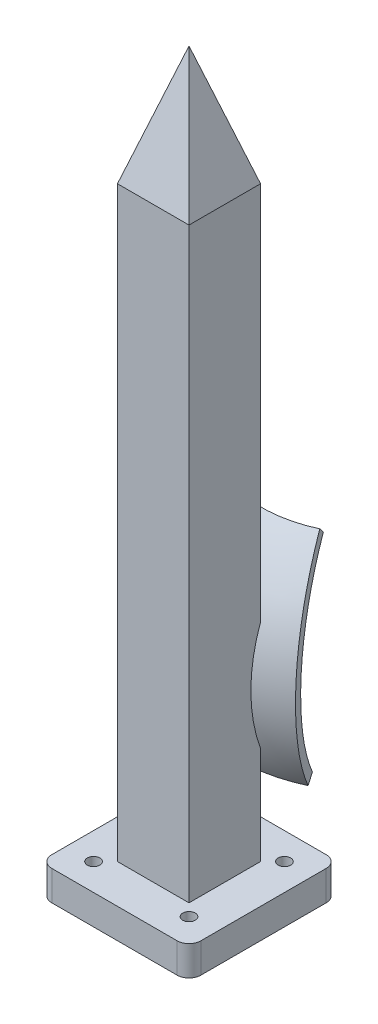
SolidWorks part; units mm, degrees
material "ABS PC"
ref_plane "Front Plane" through (0, 0, 0) normal (0, 0, 1) x (1, 0, 0)
ref_plane "Top Plane" through (0, 0, 0) normal (0, 1, 0) x (1, 0, 0)
ref_plane "Right Plane" through (0, 0, 0) normal (1, 0, 0) x (0, 0, -1)
sketch "Sketch1" plane through (0, 0, 0) normal (0, 1, 0) x (1, 0, 0)
  line L1 (0, 0) -> (25, 0)
  line L2 (0, 0) -> (0, 25)
  line L3 (0, 25) -> (25, 25)
  line L4 (25, 0) -> (25, 25)
  dimension "D1" = 25
  dimension "D2" = 25
extrude "Boss-Extrude1" add sketch "Sketch1" along normal blind 5
sketch "Sketch2" plane through (0, 5, 0) normal (0, 1, 0) x (1, 0, 0)
  line L0 (0, 0) -> (25, 0) construction
  line L1 (0, 25) -> (0, 0) construction
  line L2 (25, 0) -> (25, 25) construction
  line L3 (25, 25) -> (0, 25) construction
  circle A0 centre (4.5, 4.5) radius 1.05
  circle A1 centre (20.5, 4.5) radius 1.05
  circle A2 centre (20.5, 20.5) radius 1.05
  circle A3 centre (4.5, 20.5) radius 1.05
  dimension "D1" = 2.1
  dimension "D4" = 2.1
  dimension "D6" = 2.1
  dimension "D8" = 2.1
  dimension "D2" = 4.5
  dimension "D3" = 4.5
  dimension "D5" = 4.5
  dimension "D7" = 4.5
extrude "Cut-Extrude1" cut sketch "Sketch2" against normal blind 5
fillet "Fillet1" radius 2 4 edges at (0, 2.5, -25) (0, 2.5, 0) (25, 2.5, -25) (25, 2.5, 0)
sketch "Sketch3" plane through (0, 5, 0) normal (0, 1, 0) x (1, 0, 0)
  line L0 (2, 0) -> (23, 0) construction
  line L1 (6.5, 6.5) -> (18.5, 6.5)
  line L2 (6.5, 6.5) -> (6.5, 18.5)
  line L3 (6.5, 18.5) -> (18.5, 18.5)
  line L4 (18.5, 6.5) -> (18.5, 18.5)
  line L5 (25, 2) -> (25, 23) construction
  line L7 (9.5, 15.5) -> (15.5, 15.5)
  line L8 (9.5, 15.5) -> (9.5, 9.5)
  line L9 (9.5, 9.5) -> (15.5, 9.5)
  line L10 (15.5, 15.5) -> (15.5, 9.5)
  line L11 (9.5, 15.5) -> (15.5, 9.5) construction
  line L12 (9.5, 9.5) -> (15.5, 15.5) construction
  point P8 (12.5, 12.5)
  dimension "D1" = 12
  dimension "D2" = 6.5
  dimension "D3" = 6.5
  dimension "D4" = 6
extrude "Boss-Extrude2" add sketch "Sketch3" along normal blind 98.425
sketch "Sketch4" plane through (0, 0, 0) normal (0, -1, 0) x (-1, 0, 0)
  line L1 (-9.5, 9.5) -> (-15.5, 9.5)
  line L2 (-9.5, 9.5) -> (-9.5, 15.5)
  line L3 (-9.5, 15.5) -> (-15.5, 15.5)
  line L4 (-15.5, 9.5) -> (-15.5, 15.5)
  line L5 (-9.5, 9.5) -> (-15.5, 15.5) construction
  line L6 (-9.5, 15.5) -> (-15.5, 9.5) construction
  point P0 (-12.5, 12.5)
  dimension "D1" = 6
extrude "Cut-Extrude2" cut sketch "Sketch4" against normal blind 10
sketch "Sketch5" plane through (0, 103.425, 0) normal (0, 1, 0) x (1, 0, 0)
  line L0 (18.5, 6.5) -> (18.5, 18.5) construction
  line L1 (6.5, 6.5) -> (18.5, 6.5)
  line L2 (6.5, 6.5) -> (6.5, 18.5)
  line L3 (6.5, 18.5) -> (18.5, 18.5)
  line L4 (18.5, 6.5) -> (18.5, 18.5)
extrude "Boss-Extrude3" add sketch "Sketch5" along normal blind 20
sketch "Sketch6" plane through (0, 0, -6.5) normal (0, 0, 1) x (1, 0, 0)
  line L0 (12.5, 123.425) -> (12.5, 103.425)
  line L1 (6.5, 123.425) -> (18.5, 123.425) construction
  line L2 (12.5, 103.425) -> (18.5, 103.425)
  line L3 (18.5, 123.425) -> (18.5, 5) construction
  line L4 (18.5, 103.425) -> (12.5, 123.425)
  line L5 (18.5, 123.425) -> (18.5, 103.425)
  line L6 (12.5, 123.425) -> (6.5, 123.425)
  line L7 (6.5, 123.425) -> (6.5, 103.425)
  line L8 (6.5, 123.425) -> (6.5, 5) construction
  line L9 (6.5, 103.425) -> (12.5, 123.425)
  point P14 (6.5, 103.425)
  line M2 (18.5, 5) -> (18.5, 123.425)
  line M3 (18.5, 123.425) -> (6.5, 123.425)
  line M4 (6.5, 123.425) -> (6.5, 5)
  dimension "D1" = 20
extrude "Cut-Extrude3" cut sketch "Sketch6" against normal blind 20 contours L4 M2 M3 | L9 M4 M3
sketch "Sketch7" plane through (6.5, 0, 0) normal (-1, 0, 0) x (0, 0, 1)
  line L0 (-6.5, 103.425) -> (-12.5, 123.425)
  line L1 (-18.5, 123.425) -> (-6.5, 123.425) construction
  line L2 (-12.5, 123.425) -> (-6.5, 123.425)
  line L3 (-6.5, 123.425) -> (-6.5, 103.425)
  line L4 (-12.5, 123.425) -> (-18.5, 123.425)
  line L5 (-18.5, 123.425) -> (-18.5, 103.425)
  line L6 (-18.5, 103.425) -> (-12.5, 123.425)
extrude "Cut-Extrude4" cut sketch "Sketch7" against normal blind 20 contours L3 L2 L0 | L5 L6 L4
ref_plane "Plane1" through (12.5, 0, 0) normal (1, 0, 0) x (0, 0, -1)
sketch "Sketch8" plane through (12.5, 0, 0) normal (1, 0, 0) x (0, 0, -1)
  line L0 (20.5589, 15.786) -> (43.617, 30.6059)
  line L1 (43.617, 30.6059) -> (24.6276, 50.3723)
  line L2 (43.617, 54.7917) -> (43.617, -9.159)
  arc A0 (20.5589, 15.786) -> (24.6276, 50.3723) centre (43.617, 30.6059) cw
  arc A1 (22.0647, 16.7538) -> (25.8677, 49.0815) centre (43.617, 30.6059) cw
revolve "Revolve1" add sketch "Sketch8" angle 25 about L2 other way angle 25
